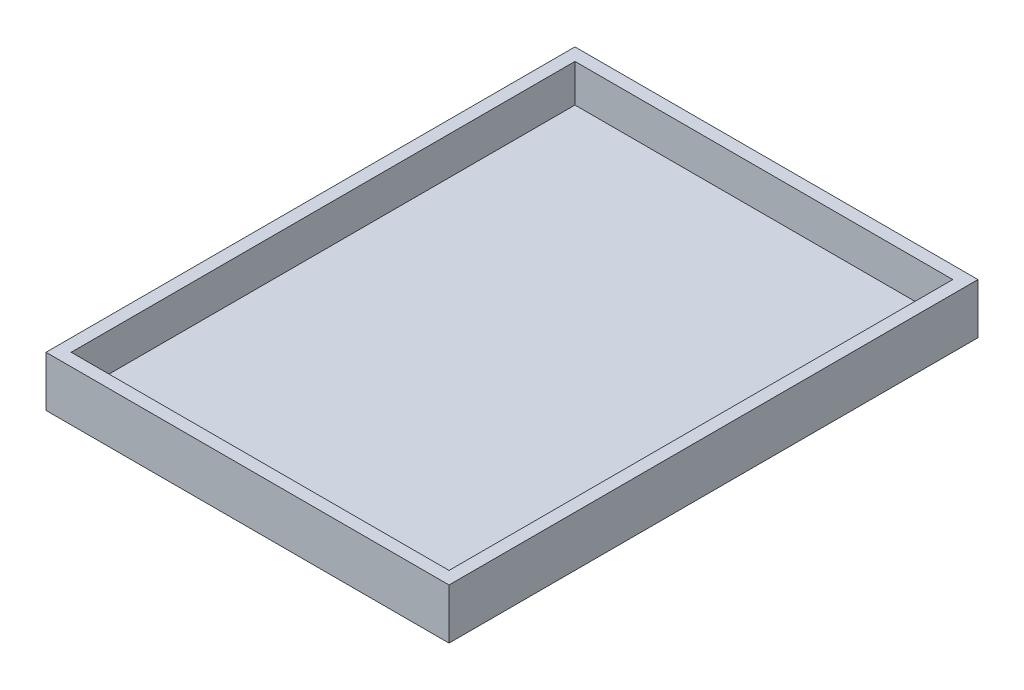
SolidWorks part; units mm, degrees
ref_plane "Front Plane" through (0, 0, 0) normal (0, 0, 1) x (1, 0, 0)
ref_plane "Top Plane" through (0, 0, 0) normal (0, 1, 0) x (1, 0, 0)
ref_plane "Right Plane" through (0, 0, 0) normal (1, 0, 0) x (0, 0, -1)
sketch "Sketch1" plane through (0, 0, 0) normal (0, 1, 0) x (1, 0, 0)
  line L1 (-80, -105) -> (80, -105)
  line L2 (-80, -105) -> (-80, 105)
  line L3 (-80, 105) -> (80, 105)
  line L4 (80, -105) -> (80, 105)
  line L5 (-80, -105) -> (80, 105) construction
  line L6 (-80, 105) -> (80, -105) construction
  point P0 (0, 0)
  dimension "D1" = 160
  dimension "D2" = 210
extrude "Boss-Extrude1" add sketch "Sketch1" along normal blind 20
shell "Shell1" thickness 5
